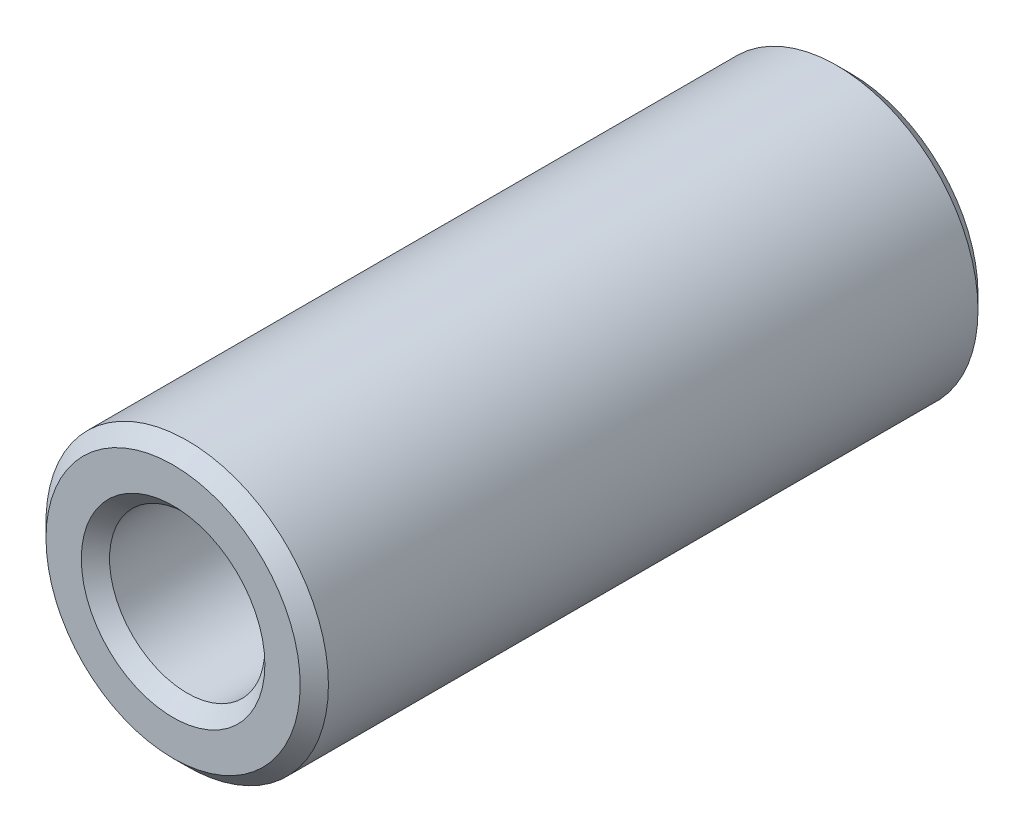
SolidWorks part; units mm, degrees
ref_plane "Front Plane" through (0, 0, 0) normal (0, 0, 1) x (1, 0, 0)
ref_plane "Top Plane" through (0, 0, 0) normal (0, 1, 0) x (1, 0, 0)
ref_plane "Right Plane" through (0, 0, 0) normal (1, 0, 0) x (0, 0, -1)
sketch "Sketch1" plane through (0, 0, 0) normal (0, 0, 1) x (1, 0, 0)
  circle A0 centre (0, 0) radius 5
  circle A1 centre (0, 0) radius 2.75
  dimension "D1" = 10
  dimension "D2" = 5.5
extrude "Boss-Extrude1" add sketch "Sketch1" along normal blind 24
chamfer "Chamfer1" distance 0.5 angle 45 4 edges at (2.75, 0, 0) (5, 0, 0) (2.75, 0, 24) (5, 0, 24)
